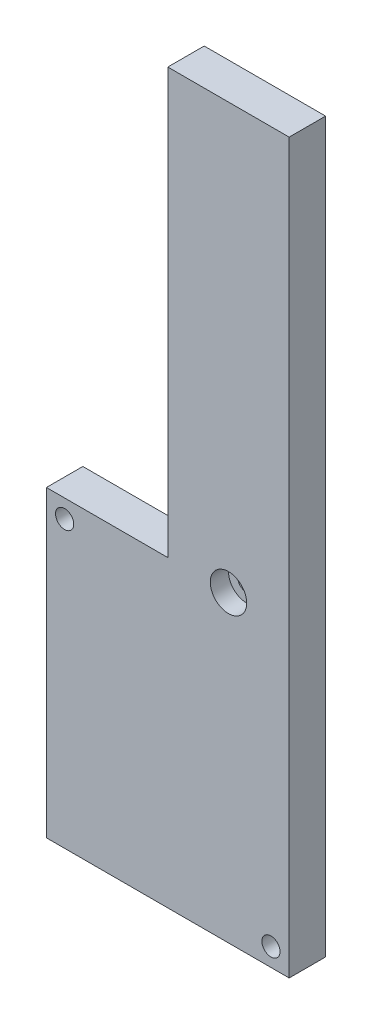
SolidWorks part; units mm, degrees
ref_plane "Plan de face" through (0, 0, 0) normal (0, 0, 1) x (1, 0, 0)
ref_plane "Plan de dessus" through (0, 0, 0) normal (0, 1, 0) x (1, 0, 0)
ref_plane "Plan de droite" through (0, 0, 0) normal (1, 0, 0) x (0, 0, -1)
sketch "Esquisse1" plane through (0, 0, 0) normal (0, 0, 1) x (1, 0, 0)
  line L1 (0, 0) -> (40, 0)
  line L2 (0, 0) -> (0, 120)
  line L3 (0, 120) -> (40, 120)
  line L4 (40, 0) -> (40, 120)
  dimension "D1" = 40
  dimension "D2" = 120
extrude "Boss.-Extru.1" add sketch "Esquisse1" along normal blind 6
sketch "Esquisse2" plane through (0, 0, 6) normal (0, 0, 1) x (1, 0, 0)
  line L1 (0, 120) -> (20, 120)
  line L2 (0, 120) -> (0, 50)
  line L3 (0, 50) -> (20, 50)
  line L4 (20, 120) -> (20, 50)
  dimension "D1" = 20
  dimension "D2" = 70
extrude "Enlèv. mat.-Extru.1" cut sketch "Esquisse2" against normal blind 6
sketch "Esquisse4" plane through (0, 0, 6) normal (0, 0, 1) x (1, 0, 0)
  line L0 (0, 50) -> (20, 50) construction
  line L1 (0, 50) -> (0, 0) construction
  line L2 (40, 0) -> (40, 120) construction
  line L3 (0, 0) -> (40, 0) construction
  circle A0 centre (3, 47) radius 1.5
  circle A1 centre (37, 3) radius 1.5
  circle A2 centre (30, 50) radius 1.5
  dimension "D1" = 3
  dimension "D2" = 3
  dimension "D3" = 3
  dimension "D4" = 3
  dimension "D5" = 3
  dimension "D6" = 3
  dimension "D7" = 10
  dimension "D8" = 50
  dimension "D9" = 3
extrude "Enlèv. mat.-Extru.2" cut sketch "Esquisse4" against normal blind 6
sketch "Esquisse5" plane through (0, 0, 6) normal (0, 0, 1) x (1, 0, 0)
  circle A0 centre (30, 50) radius 3
  dimension "D1" = 6
extrude "Enlèv. mat.-Extru.3" cut sketch "Esquisse5" against normal blind 3
